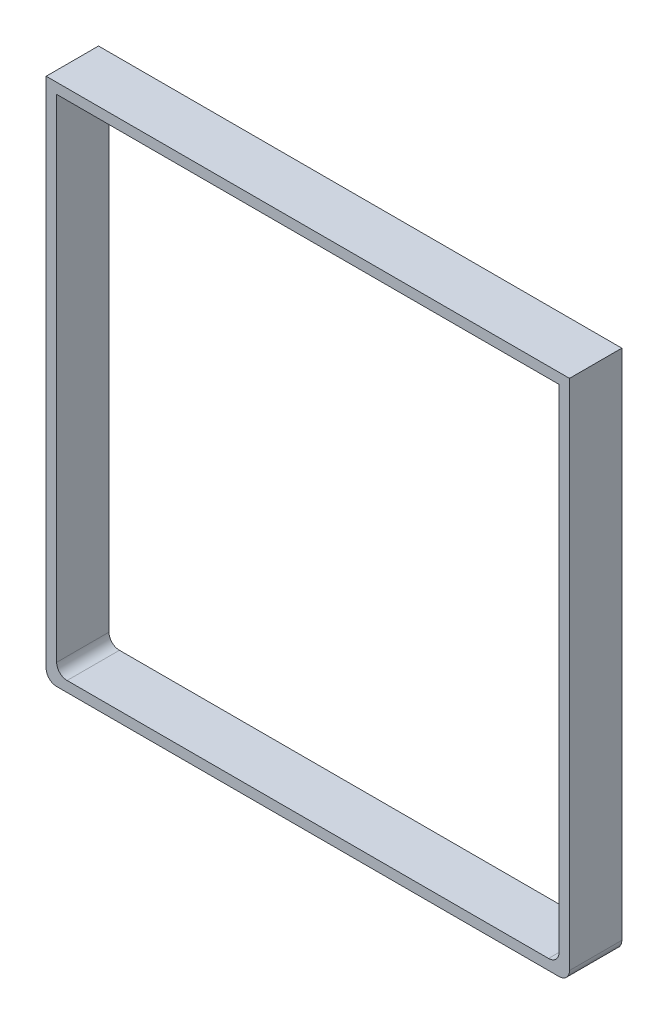
SolidWorks part; units mm, degrees
material "AISI 304"
ref_plane "Alzado" through (0, 0, 0) normal (0, 0, 1) x (1, 0, 0)
ref_plane "Planta" through (0, 0, 0) normal (0, 1, 0) x (1, 0, 0)
ref_plane "Vista lateral" through (0, 0, 0) normal (1, 0, 0) x (0, 0, -1)
sketch "Croquis2" plane through (0, 0, 0) normal (0, 0, 1) x (1, 0, 0)
  line L0 (0, 10) -> (0, 500)
  line L1 (0, 500) -> (500, 500)
  line L2 (500, 500) -> (500, 10)
  line L3 (490, 0) -> (10, 0)
  line L4 (10, 490) -> (10, 20)
  line L5 (20, 10) -> (480, 10)
  line L6 (490, 20) -> (490, 490)
  line L7 (490, 490) -> (10, 490)
  arc A0 (500, 10) -> (490, 0) centre (490, 10) cw
  arc A1 (480, 10) -> (490, 20) centre (480, 20) ccw
  arc A2 (20, 10) -> (10, 20) centre (20, 20) cw
  arc A3 (0, 10) -> (10, 0) centre (10, 10) ccw
  point P11 (500, 0)
  point P18 (0, 0)
  dimension "D7" = 10
  dimension "D1" = 500
  dimension "D2" = 500
  dimension "D3" = 10
  dimension "D4" = 10
  dimension "D5" = 10
  dimension "D6" = 10
extrude "Saliente-Extruir1" add sketch "Croquis2" along normal blind 50
